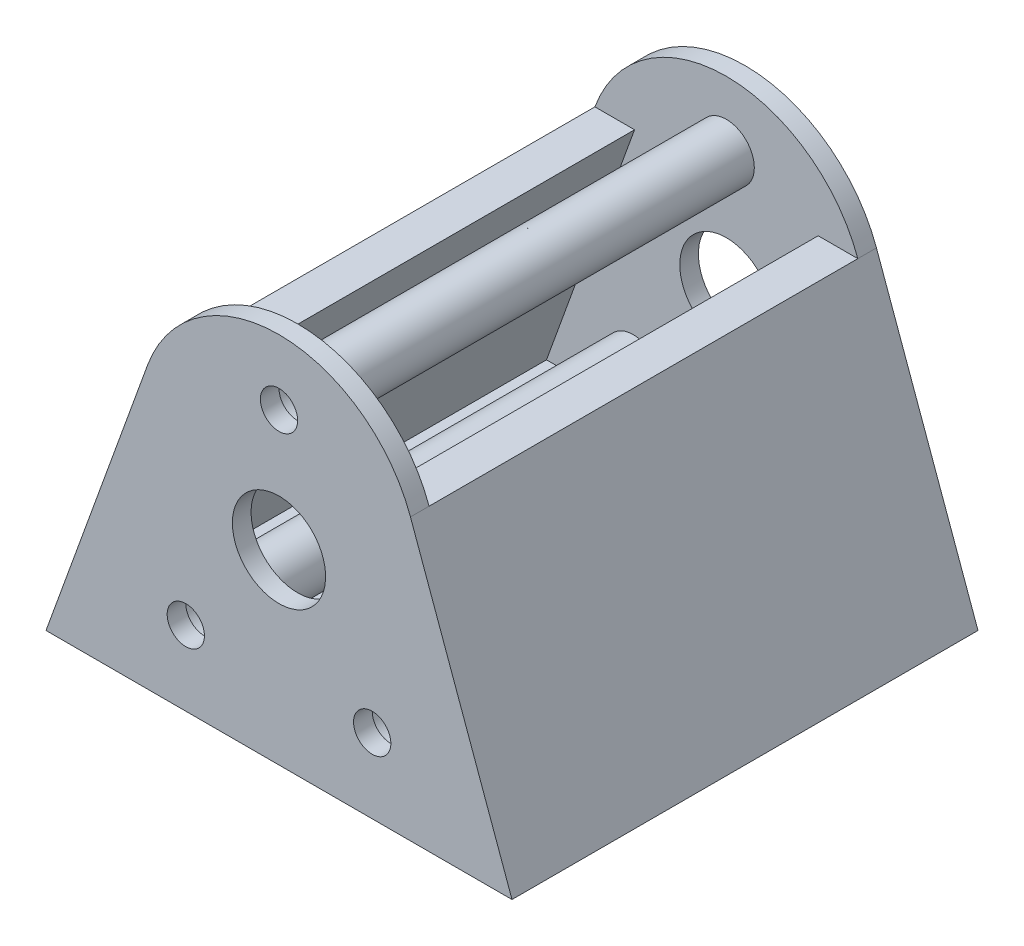
SolidWorks part; units mm, degrees
ref_plane "Front Plane" through (0, 0, 0) normal (0, 0, 1) x (1, 0, 0)
ref_plane "Top Plane" through (0, 0, 0) normal (0, 1, 0) x (1, 0, 0)
ref_plane "Right Plane" through (0, 0, 0) normal (1, 0, 0) x (0, 0, -1)
sketch "Sketch1" plane through (0, 0, 0) normal (0, 0, 1) x (1, 0, 0)
  line L0 (-25, 0) -> (25, 0)
  line L1 (0, 0) -> (0, 40) construction
  line L4 (25, 0) -> (14.1047, 30.1047)
  line L5 (-25, 0) -> (-14.1047, 30.1047)
  line L6 (-10, 8) -> (10, 8)
  arc A1 (14.1047, 30.1047) -> (-14.1047, 30.1047) centre (0, 25) ccw
  circle A2 centre (0, 20) radius 5
  circle A3 centre (-10, 8) radius 2
  circle A4 centre (10, 8) radius 2
  circle A5 centre (0, 33) radius 2
  point P4 (0, 0)
  point P14 (0, 8)
  dimension "D3" = 30
  dimension "D4" = 10
  dimension "D6" = 8
  dimension "D7" = 4
  dimension "D8" = 4
  dimension "D1" = 50
  dimension "D2" = 40
  dimension "D5" = 20
  dimension "D9" = 7
extrude "Boss-Extrude1" add sketch "Sketch1" along normal blind 2
ref_plane "Plane1" through (0, 0, 50) normal (0, 0, -1) x (-1, 0, 0)
sketch "Sketch2" plane through (0, 0, 50) normal (0, 0, -1) x (-1, 0, 0)
  line L3 (-25, 0) -> (25, 0)
  line L4 (-14.1047, 30.1047) -> (-25, 0)
  line L5 (25, 0) -> (14.1047, 30.1047)
  line L6 (-25, 0) -> (25, 0)
  line L7 (-14.1047, 30.1047) -> (-25, 0)
  line L8 (25, 0) -> (14.1047, 30.1047)
  circle A0 centre (-10, 8) radius 2 construction
  arc A1 (14.1047, 30.1047) -> (-14.1047, 30.1047) centre (0, 25) ccw
  arc A2 (14.1047, 30.1047) -> (-14.1047, 30.1047) centre (0, 25) ccw
  circle A3 centre (10, 8) radius 2 construction
  circle A4 centre (0, 33) radius 2 construction
  circle A5 centre (0, 20) radius 5 construction
  circle A6 centre (-10, 8) radius 2
  circle A7 centre (10, 8) radius 2
  circle A8 centre (0, 33) radius 2
  circle A9 centre (0, 20) radius 5
  dimension "D1" = 0
extrude "Boss-Extrude2" add sketch "Sketch2" along normal blind 2 separate body
sketch "Sketch4" plane through (0, 0, 48) normal (0, 0, -1) x (-1, 0, 0)
  line L0 (25, 0) -> (14.1047, 30.1047) construction
  line L1 (25, 0) -> (-25, 0)
  line L3 (23.5523, 4) -> (-23.5523, 4)
  line L5 (25, 0) -> (14.1047, 30.1047)
  line L6 (-14.1047, 30.1047) -> (-25, 0) construction
  line L7 (-14.1047, 30.1047) -> (-25, 0)
  line L8 (-23.5523, 4) -> (-25, 0)
  line M7 (25, 0) -> (14.1047, 30.1047)
  line M9 (-14.1047, 30.1047) -> (-25, 0)
  line M10 (-25, 0) -> (25, 0)
  dimension "D1" = 4
extrude "Boss-Extrude3" add sketch "Sketch4" along normal up to surface (46 mm away) contours L3 M7 M9 M10 up to face at (5, 20, 2)
sketch "Sketch5" plane through (0, 0, 48) normal (0, 0, -1) x (-1, 0, 0)
  line L1 (23.5523, 4) -> (14.1047, 30.1047) construction
  line L2 (19.7911, 2.6388) -> (10.3434, 28.7434)
  line L3 (19.2984, 4) -> (9.8508, 30.1047)
  line L4 (23.5523, 4) -> (14.1047, 30.1047)
  line L5 (14.1047, 30.1047) -> (9.8508, 30.1047)
  line L6 (23.5523, 4) -> (19.2984, 4)
  line L7 (23.5523, 4) -> (-23.5523, 4) construction
  line L8 (0, 0) -> (0, 53.1601) construction
  line L9 (-23.5523, 4) -> (-19.2984, 4)
  line L10 (-23.5523, 4) -> (-14.1047, 30.1047)
  line L11 (-14.1047, 30.1047) -> (-9.8508, 30.1047)
  line L12 (-19.2984, 4) -> (-9.8508, 30.1047)
  dimension "D1" = 4
sketch "Sketch7" plane through (0, 0, 48) normal (0, 0, -1) x (-1, 0, 0)
  line L0 (0, 0) -> (0, 23.8245) construction
  circle A0 centre (10, 8) radius 3
  circle A1 centre (10, 8) radius 2.5
  circle A2 centre (0, 33) radius 3
  circle A3 centre (0, 33) radius 2.5
  circle A4 centre (-10, 8) radius 2.5
  circle A5 centre (-10, 8) radius 3
  dimension "D1" = 6
  dimension "D3" = 6
  dimension "D2" = 0.5
  dimension "D4" = 0.5
extrude "Boss-Extrude4" add sketch "Sketch7" along normal up to surface (46 mm away) up to face at (0, 19.5262, 2)
extrude "Boss-Extrude5" add sketch "Sketch5" along normal up to surface (46 mm away) up to face at (13, 8, 2)
sketch "Sketch8" plane through (0, 0, 50) normal (0, 0, 1) x (1, 0, 0)
  circle A0 centre (0, 20) radius 3.0988
ref_plane "Plane2" through (0, 20, 0) normal (0, 1, 0) x (1, 0, 0)
sketch "Sketch9" plane through (0, 20, 0) normal (0, 1, 0) x (1, 0, 0)
  line L0 (0, 0) -> (0, -25) construction
  line L1 (14.1047, 0) -> (-14.1047, 0) construction
sketch "Sketch10" plane through (0, 0, 0) normal (0, -1, 0) x (1, 0, 0)
  line L0 (0, 0) -> (0, 50) construction
  line L1 (3.0988, 50) -> (-3.0988, 50) construction
  line L2 (0, 25) -> (-25, 25) construction
  line L3 (-25, 50) -> (-25, 0) construction
  line L4 (-12.5, 25) -> (-12.5, 0) construction
  line L5 (-25, 0) -> (25, 0) construction
  circle A0 centre (-12.5, 12.5) radius 5
  circle A1 centre (-12.5, 12.5) radius 2.5
  circle A2 centre (-12.5, 37.5) radius 2.5
  circle A3 centre (-12.5, 37.5) radius 5
  circle A4 centre (12.5, 12.5) radius 2.5
  circle A5 centre (12.5, 37.5) radius 2.5
  circle A6 centre (12.5, 37.5) radius 5
  circle A7 centre (12.5, 12.5) radius 5
  dimension "D1" = 10
  dimension "D2" = 5
extrude "Boss-Extrude6" add sketch "Sketch10" along normal blind 5
